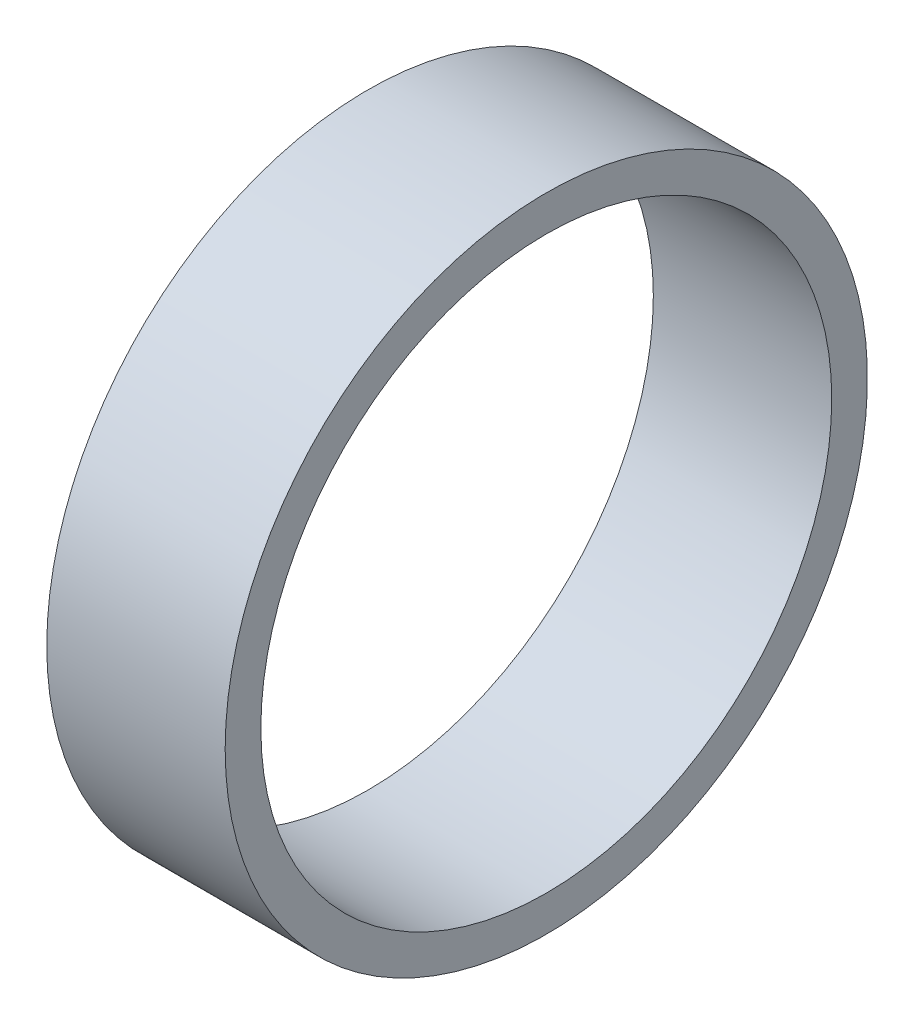
SolidWorks part; units mm, degrees
material "PPS"
ref_plane "Front Plane" through (0, 0, 0) normal (0, 0, 1) x (1, 0, 0)
ref_plane "Top Plane" through (0, 0, 0) normal (0, 1, 0) x (1, 0, 0)
ref_plane "Right Plane" through (0, 0, 0) normal (1, 0, 0) x (0, 0, -1)
sketch "Sketch1" plane through (0, 0, 0) normal (0, 1, 0) x (1, 0, 0)
  line L0 (0, 16) -> (10, 16)
  line L1 (10, 16) -> (10, 18)
  line L2 (10, 18) -> (0, 18)
  line L3 (0, 18) -> (0, 16)
  line L4 (0, 0) -> (16.3244, 0) construction
  dimension "D1" = 10
  dimension "D2" = 16
  dimension "D3" = 18
revolve "Revolve1" add sketch "Sketch1" angle 360 about L4
